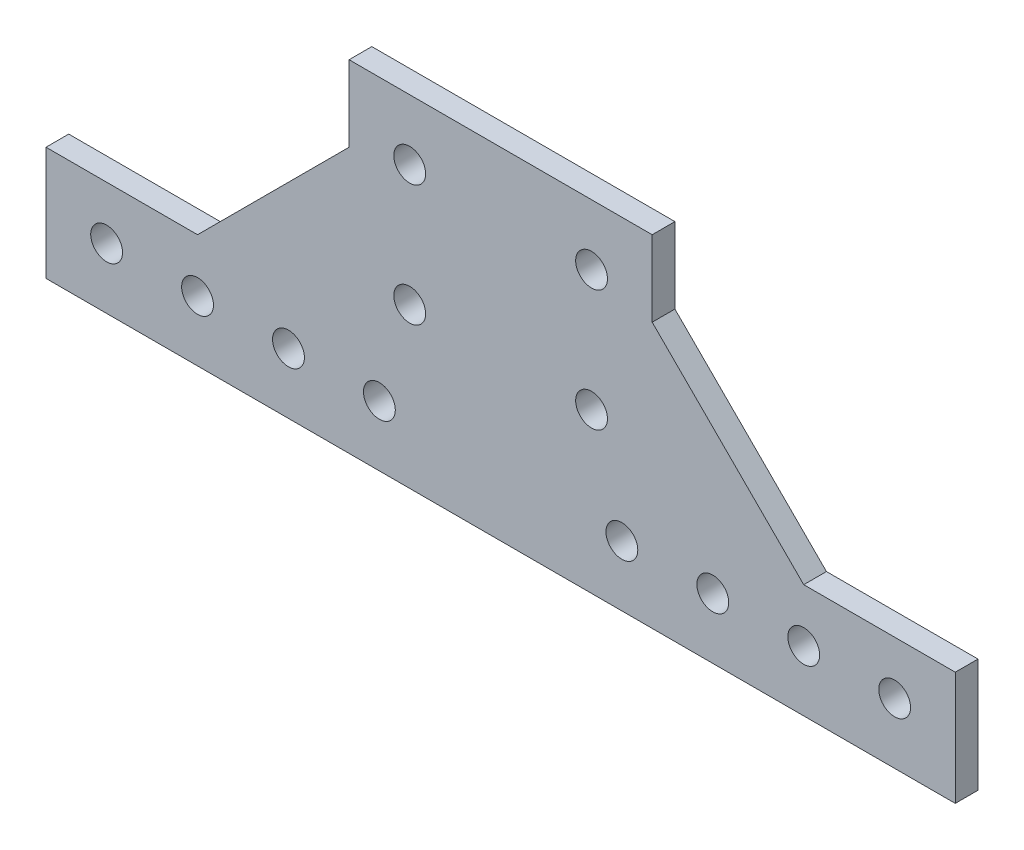
SolidWorks part; units mm, degrees
material "Thornel VCB-20 碳布"
ref_plane "前视基准面" through (0, 0, 0) normal (0, 0, 1) x (1, 0, 0)
ref_plane "上视基准面" through (0, 0, 0) normal (0, 1, 0) x (1, 0, 0)
ref_plane "右视基准面" through (0, 0, 0) normal (1, 0, 0) x (0, 0, -1)
other "Configuration Table"
sketch "草图1" plane through (0, 0, 0) normal (0, 0, 1) x (1, 0, 0)
  line L0 (0, 0) -> (120, 0)
  line L1 (120, 0) -> (120, 15)
  line L2 (120, 15) -> (100, 15)
  line L3 (100, 15) -> (80, 35)
  line L4 (80, 35) -> (80, 45)
  line L5 (80, 45) -> (40, 45)
  line L6 (40, 45) -> (40, 35)
  line L7 (40, 35) -> (20, 15)
  line L8 (20, 15) -> (0, 15)
  line L9 (0, 15) -> (0, 0)
  line L10 (80, 35) -> (80, 15) construction
  line L11 (80, 15) -> (100, 15) construction
  line L12 (40, 35) -> (40, 15) construction
  line L13 (40, 15) -> (20, 15) construction
  dimension "D1" = 135
  dimension "D2" = 135
  dimension "D3" = 40
  dimension "D4" = 15
  dimension "D5" = 30
  dimension "D6" = 40
  dimension "D7" = 20
extrude "凸台-拉伸1" add sketch "草图1" along normal blind 3
sketch "草图2" plane through (0, 0, 3) normal (0, 0, 1) x (1, 0, 0)
  line L0 (8, 8) -> (112, 8) construction
  line L1 (48, 37) -> (48, 21) construction
  line L2 (48, 21) -> (72, 21) construction
  line L3 (72, 21) -> (72, 37) construction
  line L4 (72, 37) -> (48, 37) construction
  line L10 (0, 15) -> (0, 0)
  line L11 (0, 0) -> (120, 0)
  line L12 (120, 0) -> (120, 15)
  line L13 (120, 15) -> (100, 15)
  line L14 (100, 15) -> (80, 35)
  line L15 (80, 35) -> (80, 45)
  line L16 (80, 45) -> (40, 45)
  line L17 (40, 45) -> (40, 35)
  line L18 (40, 35) -> (20, 15)
  line L19 (20, 15) -> (0, 15)
  line L20 (0, 15) -> (0, 0) construction
  line L21 (0, 0) -> (120, 0) construction
  line L22 (120, 0) -> (120, 15) construction
  line L23 (120, 15) -> (100, 15) construction
  line L24 (100, 15) -> (80, 35) construction
  line L25 (80, 35) -> (80, 45) construction
  line L26 (80, 45) -> (40, 45) construction
  line L27 (40, 45) -> (40, 35) construction
  line L28 (40, 35) -> (20, 15) construction
  line L29 (20, 15) -> (0, 15) construction
  circle A0 centre (48, 37) radius 2.1
  circle A1 centre (72, 37) radius 2.1
  circle A2 centre (48, 21) radius 2.1
  circle A3 centre (72, 21) radius 2.1
  circle A4 centre (8, 8) radius 2.1
  circle A5 centre (20, 8) radius 2.1
  circle A6 centre (100, 8) radius 2.1
  circle A7 centre (112, 8) radius 2.1
  dimension "D2" = 4.2
  dimension "D3" = 8
  dimension "D4" = 12
  dimension "D5" = 12
  dimension "D6" = 8
  dimension "D7" = 8
  dimension "D8" = 24
  dimension "D9" = 16
  dimension "D10" = 8
  dimension "D11" = 8
  dimension "D1" = 0
extrude "切除-拉伸1" cut sketch "草图2" against normal blind 3
sketch "草图3" plane through (0, 0, 3) normal (0, 0, 1) x (1, 0, 0)
  line L0 (8, 8) -> (112, 8) construction
  circle A0 centre (32, 8) radius 2.1
  circle A1 centre (44, 8) radius 2.1
  circle A2 centre (76, 8) radius 2.1
  circle A3 centre (88, 8) radius 2.1
  circle A4 centre (20, 8) radius 2.1 construction
  circle A5 centre (100, 8) radius 2.1 construction
  dimension "D1" = 4.2
  dimension "D3" = 12
  dimension "D4" = 12
  dimension "D5" = 12
  dimension "D2" = 12
extrude "切除-拉伸2" cut sketch "草图3" against normal through all
